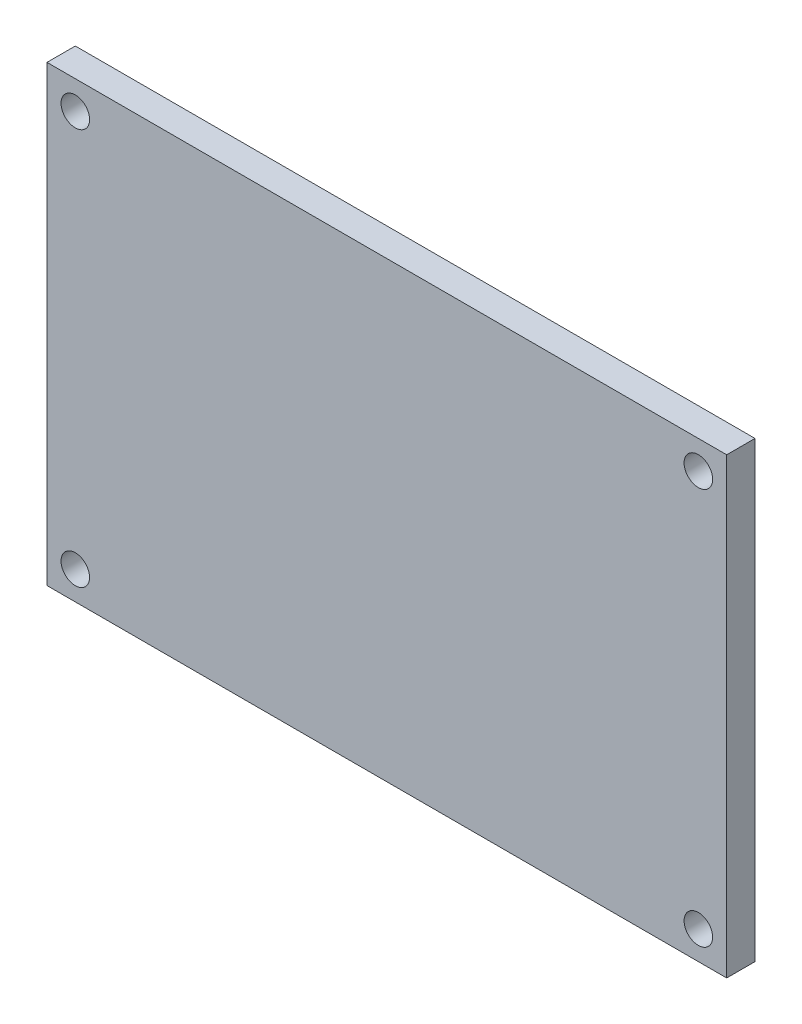
SolidWorks part; units mm, degrees
ref_plane "Front Plane" through (0, 0, 0) normal (0, 0, 1) x (1, 0, 0)
ref_plane "Top Plane" through (0, 0, 0) normal (0, 1, 0) x (1, 0, 0)
ref_plane "Right Plane" through (0, 0, 0) normal (1, 0, 0) x (0, 0, -1)
sketch "Sketch1" plane through (0, 0, 0) normal (0, 0, 1) x (1, 0, 0)
  line L1 (-38.1, -25.4) -> (38.1, -25.4)
  line L2 (-38.1, -25.4) -> (-38.1, 25.4)
  line L3 (-38.1, 25.4) -> (38.1, 25.4)
  line L4 (38.1, -25.4) -> (38.1, 25.4)
  line L5 (-38.1, -25.4) -> (38.1, 25.4) construction
  line L6 (-38.1, 25.4) -> (38.1, -25.4) construction
  point P0 (0, 0)
  dimension "D1" = 76.2
  dimension "D2" = 50.8
extrude "Boss-Extrude1" add sketch "Sketch1" along normal blind 3.175
sketch "Sketch2" plane through (0, 0, 3.175) normal (0, 0, 1) x (1, 0, 0)
  line L0 (0, 0) -> (0, 25.4) construction
  line L1 (38.1, 25.4) -> (-38.1, 25.4) construction
  line L2 (-38.1, 25.4) -> (-38.1, -25.4) construction
  line L3 (-38.1, -25.4) -> (38.1, -25.4) construction
  circle A0 centre (-34.925, 22.225) radius 1.6
  circle A1 centre (-34.925, -22.225) radius 1.6
  circle A2 centre (34.925, -22.225) radius 1.6
  circle A3 centre (34.925, 22.225) radius 1.6
  dimension "D5" = 3.2
  dimension "D6" = 3.2
  dimension "D1" = 3.175
  dimension "D2" = 3.175
  dimension "D3" = 3.175
  dimension "D4" = 3.175
extrude "Cut-Extrude1" cut sketch "Sketch2" against normal up to next
